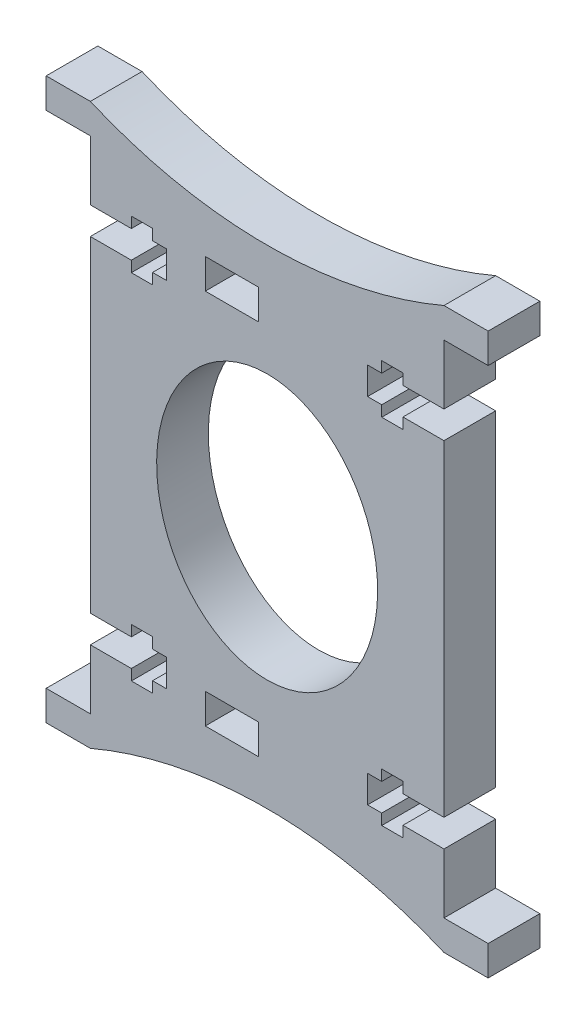
SolidWorks part; units mm, degrees
material "Acrylic (Medium-high impact)"
ref_plane "Front Plane" through (0, 0, 0) normal (0, 0, 1) x (1, 0, 0)
ref_plane "Top Plane" through (0, 0, 0) normal (0, 1, 0) x (1, 0, 0)
ref_plane "Right Plane" through (0, 0, 0) normal (1, 0, 0) x (0, 0, -1)
sketch "Sketch1" plane through (0, 0, 0) normal (0, 0, 1) x (1, 0, 0)
  line L0 (20, 0) -> (-20, 0) construction
  line L1 (15.3618, -20) -> (20, -20) construction
  line L2 (15.3618, -20) -> (15.3618, -21.5478) construction
  line L3 (15.3618, -18.4522) -> (15.3618, -20) construction
  line L4 (14.1618, -22.7722) -> (14.1618, -20) construction
  line L5 (11.3618, -20) -> (20, -20) construction
  line L6 (14.1618, -17.2278) -> (14.1618, -20) construction
  line L7 (12.9618, -22.7722) -> (15.3618, -22.7722)
  line L8 (-20, 0) -> (-20, -18.4522)
  line L9 (-14.1618, -17.2278) -> (-14.1618, -20) construction
  line L10 (12.9618, -17.2278) -> (15.3618, -17.2278)
  line L11 (11.3618, -18.4522) -> (11.3618, -21.5478)
  line L12 (20, -21.5478) -> (20, -28.31)
  line L13 (20, -21.5478) -> (15.3618, -21.5478)
  line L14 (15.3618, -18.4522) -> (20, -18.4522)
  line L15 (25, -31.69) -> (25, -28.31)
  line L16 (20, -31.69) -> (25, -31.69)
  line L17 (-11.3618, -20) -> (-20, -20) construction
  line L18 (-12.9618, -22.7722) -> (-12.9618, -21.5478)
  line L19 (-12.9618, -18.4522) -> (-11.3618, -18.4522)
  line L20 (-12.9618, -21.5478) -> (-11.3618, -21.5478)
  line L21 (-12.9618, -18.4522) -> (-12.9618, -17.2278)
  line L22 (-14.1618, -22.7722) -> (-14.1618, -20) construction
  line L23 (-15.3618, -22.7722) -> (-15.3618, -21.5478)
  line L24 (-15.3618, -18.4522) -> (-15.3618, -17.2278)
  line L25 (-15.3618, -18.4522) -> (-15.3618, -20) construction
  line L26 (-15.3618, -20) -> (-15.3618, -21.5478) construction
  line L27 (-25, -28.31) -> (-20, -28.31)
  line L28 (-20, -31.69) -> (-25, -31.69)
  line L29 (-25, -31.69) -> (-25, -28.31)
  line L30 (-15.3618, -18.4522) -> (-20, -18.4522)
  line L31 (-20, -21.5478) -> (-15.3618, -21.5478)
  line L32 (-20, -21.5478) -> (-20, -28.31)
  line L33 (-15.3618, -20) -> (-20, -20) construction
  line L34 (-11.3618, -18.4522) -> (-11.3618, -21.5478)
  line L35 (25, -28.31) -> (20, -28.31)
  line L36 (15.3618, -18.4522) -> (15.3618, -17.2278)
  line L37 (15.3618, -22.7722) -> (15.3618, -21.5478)
  line L38 (12.9618, -18.4522) -> (12.9618, -17.2278)
  line L39 (12.9618, -21.5478) -> (11.3618, -21.5478)
  line L40 (12.9618, -18.4522) -> (11.3618, -18.4522)
  line L41 (12.9618, -22.7722) -> (12.9618, -21.5478)
  line L42 (20, 0) -> (20, -18.4522)
  line L43 (-15.3618, 20) -> (-20, 20) construction
  line L44 (-12.9618, -17.2278) -> (-15.3618, -17.2278)
  line L45 (-15.3618, 20) -> (-15.3618, 21.5478) construction
  line L46 (-15.3618, 18.4522) -> (-15.3618, 20) construction
  line L47 (-14.1618, 22.7722) -> (-14.1618, 20) construction
  line L48 (-11.3618, 20) -> (-20, 20) construction
  line L49 (-14.1618, 17.2278) -> (-14.1618, 20) construction
  line L50 (14.1618, 17.2278) -> (14.1618, 20) construction
  line L51 (11.3618, 20) -> (20, 20) construction
  line L52 (14.1618, 22.7722) -> (14.1618, 20) construction
  line L53 (15.3618, 18.4522) -> (15.3618, 20) construction
  line L54 (15.3618, 20) -> (15.3618, 21.5478) construction
  line L55 (15.3618, 20) -> (20, 20) construction
  line L56 (-12.9618, 22.7722) -> (-15.3618, 22.7722)
  line L57 (-12.9618, 17.2278) -> (-15.3618, 17.2278)
  line L58 (20, 0) -> (20, 18.4522)
  line L59 (12.9618, 22.7722) -> (12.9618, 21.5478)
  line L60 (0, -540.4392) -> (0, 49459.5608) construction
  line L61 (-12.9618, -22.7722) -> (-15.3618, -22.7722)
  line L62 (12.9618, 18.4522) -> (11.3618, 18.4522)
  line L63 (12.9618, 21.5478) -> (11.3618, 21.5478)
  line L64 (12.9618, 18.4522) -> (12.9618, 17.2278)
  line L65 (15.3618, 22.7722) -> (15.3618, 21.5478)
  line L66 (15.3618, 18.4522) -> (15.3618, 17.2278)
  line L67 (25, 28.31) -> (20, 28.31)
  line L68 (-11.3618, 18.4522) -> (-11.3618, 21.5478)
  line L69 (-20, 21.5478) -> (-20, 28.31)
  line L70 (-20, 21.5478) -> (-15.3618, 21.5478)
  line L71 (-15.3618, 18.4522) -> (-20, 18.4522)
  line L72 (-25, 31.69) -> (-25, 28.31)
  line L73 (-20, 31.69) -> (-25, 31.69)
  line L74 (-25, 28.31) -> (-20, 28.31)
  line L75 (-15.3618, 18.4522) -> (-15.3618, 17.2278)
  line L76 (-15.3618, 22.7722) -> (-15.3618, 21.5478)
  line L77 (-12.9618, 18.4522) -> (-12.9618, 17.2278)
  line L78 (-12.9618, 21.5478) -> (-11.3618, 21.5478)
  line L79 (-12.9618, 18.4522) -> (-11.3618, 18.4522)
  line L80 (-12.9618, 22.7722) -> (-12.9618, 21.5478)
  line L81 (20, 31.69) -> (25, 31.69)
  line L82 (25, 31.69) -> (25, 28.31)
  line L83 (15.3618, 18.4522) -> (20, 18.4522)
  line L84 (20, 21.5478) -> (15.3618, 21.5478)
  line L85 (20, 21.5478) -> (20, 28.31)
  line L86 (11.3618, 18.4522) -> (11.3618, 21.5478)
  line L87 (12.9618, 17.2278) -> (15.3618, 17.2278)
  line L88 (-20, 0) -> (-20, 18.4522)
  line L89 (12.9618, 22.7722) -> (15.3618, 22.7722)
  line L90 (0, 0) -> (-13.5, 0) construction
  line L91 (-20, 21.5478) -> (-20, 18.4522) construction
  line L92 (-20, 28.31) -> (-20, 31.69) construction
  line L93 (-20, -28.31) -> (-20, -31.69) construction
  line L94 (-20, 31.69) -> (20, 31.69) construction
  line L95 (-20, -31.69) -> (20, -31.69) construction
  line L96 (20, 21.5478) -> (20, 18.4522) construction
  line L97 (20, -18.4522) -> (20, -21.5478) construction
  line L98 (-1, 21.3) -> (-7, 21.3) construction
  line L99 (-1, 19.6) -> (-7, 19.6)
  line L100 (-1, 19.6) -> (-1, 23)
  line L101 (-1, 23) -> (-7, 23)
  line L102 (-7, 19.6) -> (-7, 23)
  line L103 (-1, 19.6) -> (-7, 23) construction
  line L104 (-1, 23) -> (-7, 19.6) construction
  line L105 (-7, -19.6) -> (-7, -23)
  line L106 (-1, -19.6) -> (-7, -19.6)
  line L107 (-1, -23) -> (-7, -23)
  line L108 (-1, -19.6) -> (-1, -23)
  arc A0 (-20, 31.69) -> (20, 31.69) centre (0, 78.5448) ccw
  arc A1 (-20, -31.69) -> (20, -31.69) centre (0, -78.5448) cw
  ellipse E0 centre (0, 0) end of major axis (0, 15) minor radius 12.5
  point P30 (0, 15)
  point P38 (0, 0)
  point P97 (0, 27.6)
  point P102 (-20, 30)
  point P103 (-20, -30)
  point P105 (0, -15)
  point P106 (-4, 21.3)
  dimension "D9" = 16
  dimension "D13" = 6
  dimension "D1" = 60
  dimension "D2" = 3.0957
  dimension "D3" = 3.38
  dimension "D4" = 10
  dimension "D5" = 1.6
  dimension "D6" = 40
  dimension "D7" = 2.4
  dimension "D8" = 1.2244
  dimension "D10" = 5
  dimension "D11" = 4.6
  dimension "D12" = 25
  dimension "D14" = 3.4
  dimension "D15" = 4.6382
  dimension "D16" = 15
extrude "Boss-Extrude1" add sketch "Sketch1" along normal blind 5.85
